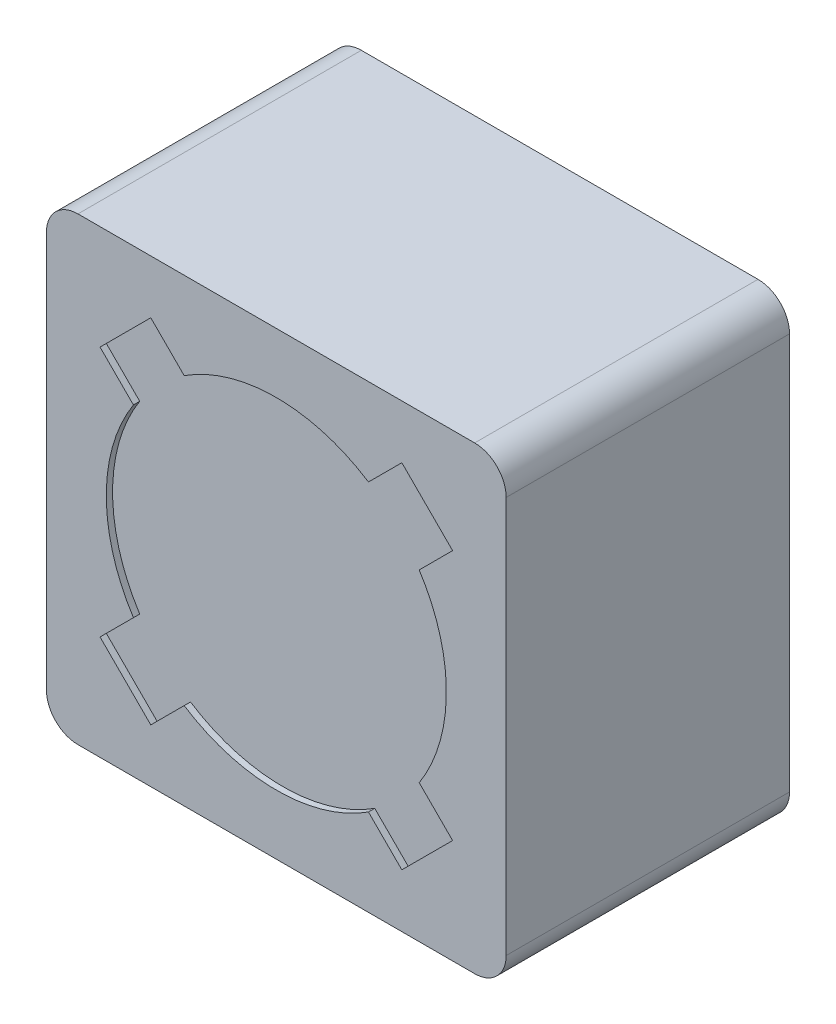
SolidWorks part; units mm, degrees
other "Детальный элемент1"
ref_plane "Спереди" through (0, 0, 0) normal (0, 0, 1) x (1, 0, 0)
ref_plane "Сверху" through (0, 0, 0) normal (0, 1, 0) x (1, 0, 0)
ref_plane "Справа" through (0, 0, 0) normal (1, 0, 0) x (0, 0, -1)
sketch "Эскиз1" plane through (0, 0, 0) normal (0, 0, 1) x (1, 0, 0)
  line L1 (-3.65, -3.65) -> (3.65, -3.65)
  line L2 (-3.65, -3.65) -> (-3.65, 3.65)
  line L3 (-3.65, 3.65) -> (3.65, 3.65)
  line L4 (3.65, -3.65) -> (3.65, 3.65)
  line L5 (-3.65, -3.65) -> (3.65, 3.65) construction
  line L6 (-3.65, 3.65) -> (3.65, -3.65) construction
  point P0 (0, 0)
  dimension "D1" = 7.3
extrude "Бобышка-Вытянуть1" add sketch "Эскиз1" along normal blind 4.5
fillet "Скругление1" radius 0.5 4 edges at (-3.65, -3.65, 2.25) (3.65, -3.65, 2.25) (-3.65, 3.65, 2.25) (3.65, 3.65, 2.25)
sketch "Эскиз2" plane through (0, 0, 4.5) normal (0, 0, 1) x (1, 0, 0)
  circle A0 centre (0, 0) radius 2.7
  dimension "D1" = 5.4
extrude "Вырез-Вытянуть1" cut sketch "Эскиз2" against normal blind 0.1
sketch "Эскиз3" plane through (0, 0, 4.5) normal (0, 0, 1) x (1, 0, 0)
  line L0 (0, 0) -> (-5.2883, 5.2883) construction
  line L1 (0, 0) -> (0, 5.819) construction
  line L2 (-2.7995, 1.9934) -> (-2.2692, 1.4631)
  line L3 (-2.7995, 1.9934) -> (-1.9934, 2.7995)
  line L4 (-2.2692, 1.4631) -> (-1.4631, 2.2692)
  line L5 (-1.9934, 2.7995) -> (-1.4631, 2.2692)
  line L6 (-2.7995, 1.9934) -> (-1.4631, 2.2692) construction
  line L7 (-2.2692, 1.4631) -> (-1.9934, 2.7995) construction
  circle A0 centre (0, 0) radius 2.7 construction
  point P3 (0, 0)
  point P5 (-2.1313, 2.1313)
  point P12 (0, 0)
  point P13 (0, 0)
  dimension "D1" = 45
  dimension "D2" = 0.75
  dimension "D3" = 1.14
extrude "Вырез-Вытянуть2" cut sketch "Эскиз3" against normal blind 0.1
pattern_circular "Круговой массив1" count 4 over 360 about axis through (0, 0, 0) along (0, 0, 1) of "Вырез-Вытянуть2"
